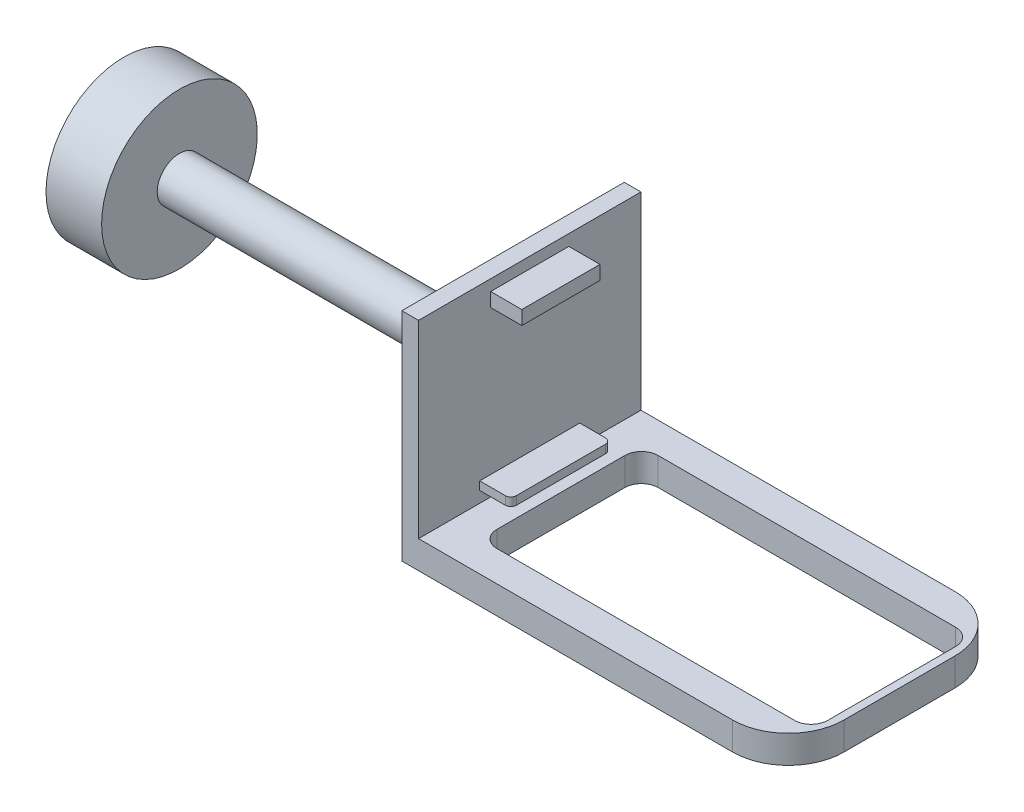
SolidWorks part; units mm, degrees
ref_plane "Front Plane" through (0, 0, 0) normal (0, 0, 1) x (1, 0, 0)
ref_plane "Top Plane" through (0, 0, 0) normal (0, 1, 0) x (1, 0, 0)
ref_plane "Right Plane" through (0, 0, 0) normal (1, 0, 0) x (0, 0, -1)
sketch "Sketch2" plane through (0, 0, 0) normal (0, 1, 0) x (1, 0, 0)
  line L0 (-27.65, 11.5) -> (-27.65, -11.5)
  line L7 (-33.25, -20) -> (33.25, -20)
  line L8 (-33.25, -20) -> (-33.25, 20)
  line L9 (-33.25, 20) -> (33.25, 20)
  line L10 (33.25, -20) -> (33.25, 20)
  line L11 (-24.65, 14.5) -> (28.85, 14.5)
  line L12 (31.85, 11.5) -> (31.85, -11.5)
  line L13 (28.85, -14.5) -> (-24.65, -14.5)
  arc A4 (31.85, -11.5) -> (28.85, -14.5) centre (28.85, -11.5) cw
  arc A5 (28.85, 14.5) -> (31.85, 11.5) centre (28.85, 11.5) cw
  arc A6 (-27.65, 11.5) -> (-24.65, 14.5) centre (-24.65, 11.5) cw
  arc A7 (-27.65, -11.5) -> (-24.65, -14.5) centre (-24.65, -11.5) ccw
  point P0 (0, 0)
  point P7 (0, 0)
  dimension "D1" = 3
extrude "Boss-Extrude1" add sketch "Sketch2" along normal blind 5
sketch "Sketch5" plane through (-33.25, 0, 0) normal (-1, 0, 0) x (0, 0, 1)
  line L1 (20, 0) -> (-20, 0)
  line L2 (20, 0) -> (20, 39)
  line L3 (20, 39) -> (-20, 39)
  line L4 (-20, 0) -> (-20, 39)
  dimension "D1" = 39
extrude "Boss-Extrude3" add sketch "Sketch5" along normal blind 3
sketch "Sketch11" plane through (-33.25, 0, 0) normal (1, 0, 0) x (0, 0, -1)
  line L6 (0, 37) -> (-7.025, 37)
  line L7 (0, 37) -> (7.025, 37)
  line L11 (-7.025, 37) -> (-7.025, 34.5)
  line L12 (-7.025, 34.5) -> (7.025, 34.5)
  line L13 (7.025, 34.5) -> (7.025, 37)
  line L14 (0, 7) -> (-9, 7)
  line L15 (0, 7) -> (9, 7)
  line L16 (9, 7) -> (9, 8.5)
  line L17 (9, 8.5) -> (-9, 8.5)
  line L18 (-9, 8.5) -> (-9, 7)
extrude "Boss-Extrude4" add sketch "Sketch11" along normal blind 5.6
fillet "Fillet4" radius 1 2 edges at (-27.65, 7.75, 9) (-27.65, 7.75, -9)
sketch "Sketch12" plane through (-36.25, 0, 0) normal (-1, 0, 0) x (0, 0, 1)
  circle A0 centre (0, 19.5) radius 4
extrude "Boss-Extrude5" add sketch "Sketch12" along normal blind 60
fillet "Fillet6" radius 10 2 edges at (33.25, 2.5, 20) (33.25, 2.5, -20)
sketch "Sketch13" plane through (-96.25, 0, 0) normal (-1, 0, 0) x (0, 0, 1)
  circle A0 centre (0, 19.5) radius 14
extrude "Boss-Extrude6" add sketch "Sketch13" along normal blind 10
sketch "Sketch14" plane through (-106.25, 0, 0) normal (-1, 0, 0) x (0, 0, 1)
  circle A0 centre (0, 19.5) radius 5
extrude "Cut-Extrude1" cut sketch "Sketch14" against normal blind 5
sketch "Sketch15" plane through (-101.25, 0, 0) normal (-1, 0, 0) x (0, 0, 1)
  circle A0 centre (0, 19.5) radius 2.25
extrude "Cut-Extrude2" cut sketch "Sketch15" against normal blind 3
